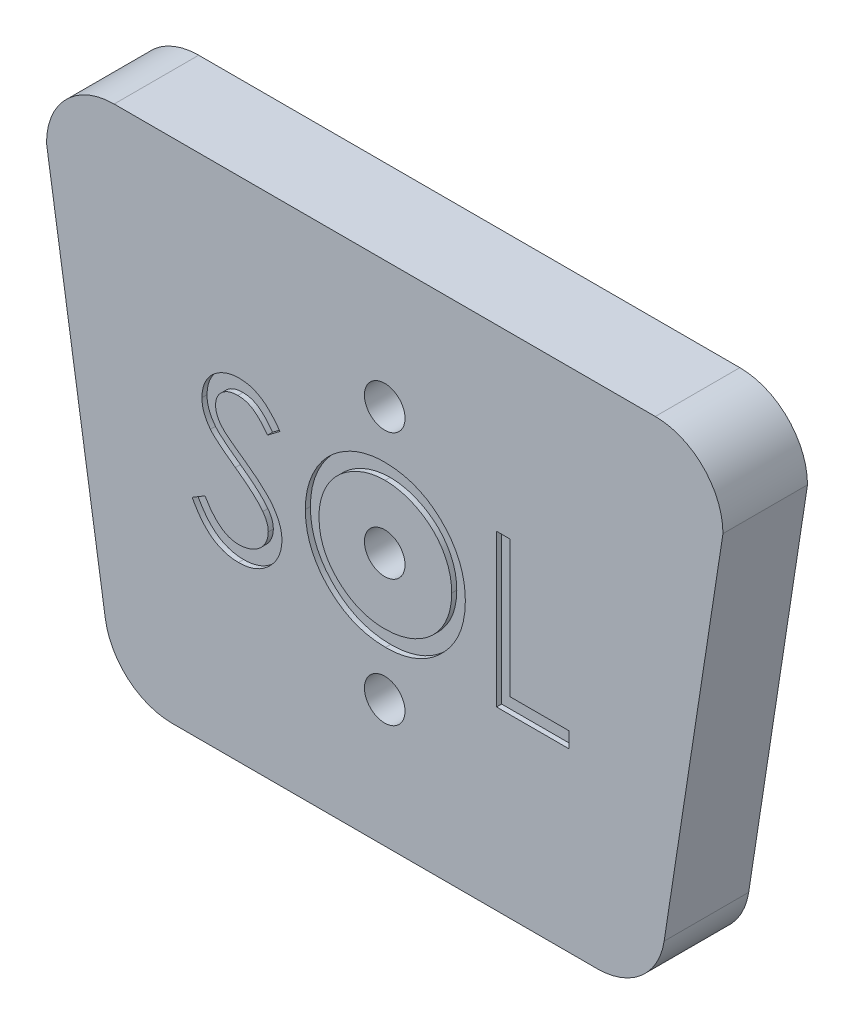
SolidWorks part; units mm, degrees
ref_plane "Front Plane" through (0, 0, 0) normal (0, 0, 1) x (1, 0, 0)
ref_plane "Top Plane" through (0, 0, 0) normal (0, 1, 0) x (1, 0, 0)
ref_plane "Right Plane" through (0, 0, 0) normal (1, 0, 0) x (0, 0, -1)
sketch "Sketch2" plane through (0, 0, 0) normal (0, 0, 1) x (1, 0, 0)
  line L0 (20, -150) -> (180, -150)
  line L1 (40, 0) -> (160, 0)
  line L3 (40, -150) -> (160, -150)
  line L6 (180, 0) -> (20, 0)
  line L8 (0, -20) -> (20, -150)
  line L9 (200, -20) -> (180, -150)
  arc A4 (200, -20) -> (180, 0) centre (180, -20) ccw
  arc A5 (0, -20) -> (20, 0) centre (20, -20) cw
  point P2 (200, 0)
  point P7 (0, -150)
  point P12 (200, 0)
  point P15 (0, 0)
  point P21 (0, 0)
  dimension "D3" = 20
  dimension "D1" = 200
  dimension "D2" = 150
extrude "Boss-Extrude1" add sketch "Sketch2" along normal blind 25 contours A5 L8 L0 L9 A4 L6 L1
fillet "Fillet2" radius 20 2 edges at (180, -150, 12.5) (20, -150, 12.5)
sketch "Sketch10" plane through (0, 0, 25) normal (0, 0, 1) x (1, 0, 0)
  line L0 (100, 0) -> (100, -150) construction
  line L1 (180, 0) -> (20, 0) construction
  line L2 (37.1584, -150) -> (162.8416, -150) construction
  line L3 (100, 0) -> (100, -75) construction
  line L4 (100, -75) -> (100, -150) construction
  line L5 (100, 0) -> (100, -75) construction
  circle A0 centre (100, -75) radius 6
  circle A1 centre (100, -112.5) radius 6
  circle A2 centre (100, -37.5) radius 6
  dimension "D1" = 12
extrude "Cut-Extrude6" cut sketch "Sketch10" against normal blind 12
sketch "Sketch11" plane through (0, 0, 13) normal (0, 0, 1) x (1, 0, 0)
  circle A0 centre (100, -37.5) radius 3.2
  circle A1 centre (100, -75) radius 3.2
  circle A2 centre (100, -112.5) radius 3.2
  dimension "D1" = 6.4
extrude "Cut-Extrude7" cut sketch "Sketch11" against normal through all
sketch "Sketch13" plane through (0, 0, 25) normal (0, 0, 1) x (1, 0, 0)
  text T0 "SOL" font "Century Gothic" height 45
extrude "Cut-Extrude8" cut sketch "Sketch13" against normal blind 1.5
